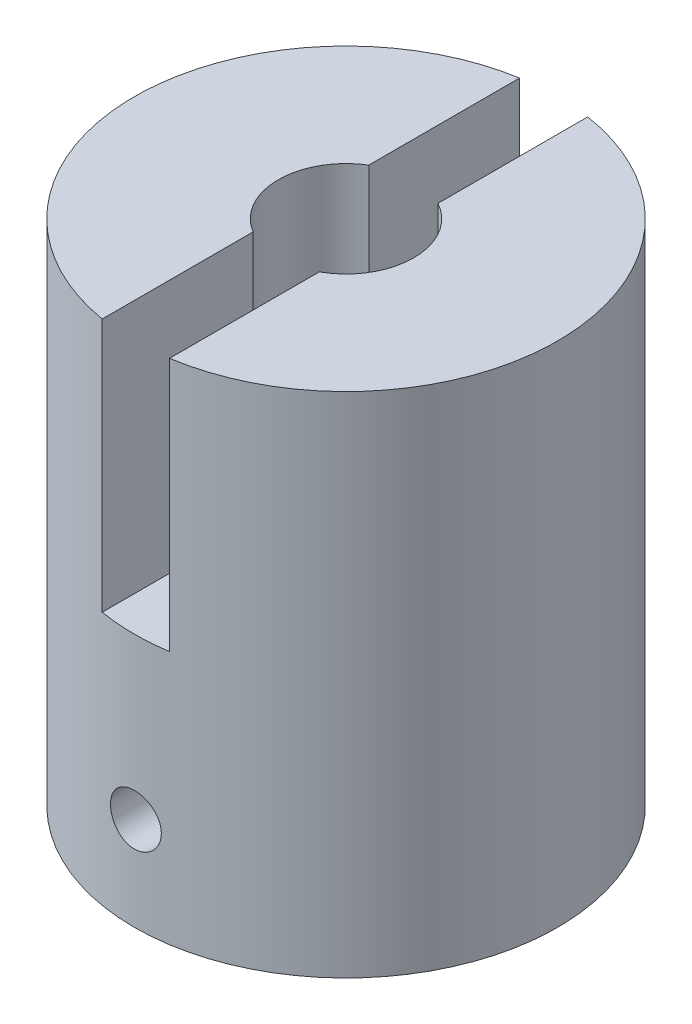
SolidWorks part; units mm, degrees
ref_plane "Alzado" through (0, 0, 0) normal (0, 0, 1) x (1, 0, 0)
ref_plane "Planta" through (0, 0, 0) normal (0, 1, 0) x (1, 0, 0)
ref_plane "Vista lateral" through (0, 0, 0) normal (1, 0, 0) x (0, 0, -1)
sketch "Croquis1" plane through (0, 0, 0) normal (0, 1, 0) x (1, 0, 0)
  circle A0 centre (0, 0) radius 12.5
  dimension "D1" = 25
extrude "Saliente-Extruir1" add sketch "Croquis1" along normal blind 30
sketch "Croquis2" plane through (0, 30, 0) normal (0, 1, 0) x (1, 0, 0)
  line L0 (-2.0738, 3.4204) -> (-2.0738, 12.8561)
  line L1 (-2.0738, -12.7724) -> (1.9262, -12.7724)
  line L2 (-2.0738, -12.7724) -> (-2.0738, -3.4204)
  line L3 (-2.0738, 12.8561) -> (1.9262, 12.8561)
  line L4 (1.9262, -12.7724) -> (1.9262, -3.5057)
  line L8 (1.9262, 3.5057) -> (1.9262, 12.8561)
  arc A0 (-2.0738, 3.4204) -> (-2.0738, -3.4204) centre (0, 0) ccw
  arc A3 (1.9262, -3.5057) -> (1.9262, 3.5057) centre (0, 0) ccw
  point P1 (-2.0738, 12.3507)
  dimension "D1" = 8
  dimension "D2" = 4
extrude "Cortar-Extruir1" cut sketch "Croquis2" against normal blind 15
sketch "Croquis3" plane through (0, 0, 0) normal (0, -1, 0) x (1, 0, 0)
  circle A0 centre (0, 0) radius 3.5
  dimension "D1" = 7
extrude "Cortar-Extruir2" cut sketch "Croquis3" against normal blind 15
ref_plane "Plano1" through (0, 0, 15) normal (0, 0, 1) x (1, 0, 0)
sketch "Croquis4" plane through (0, 0, 15) normal (0, 0, 1) x (1, 0, 0)
  circle A0 centre (0, 5.5107) radius 1.5
  dimension "D1" = 3
extrude "Cortar-Extruir3" cut sketch "Croquis4" against normal blind 15
